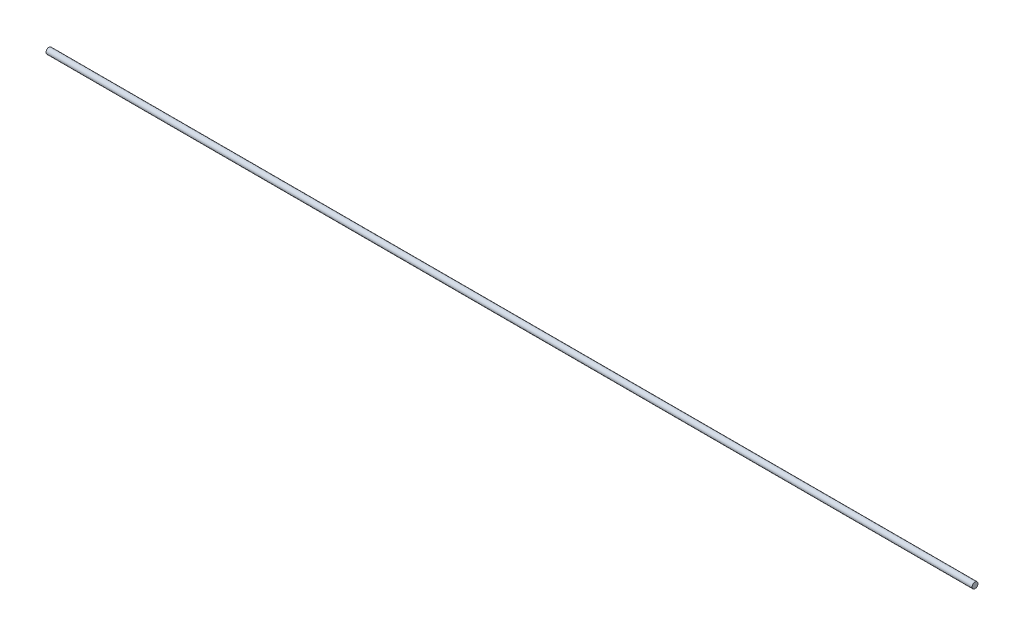
SolidWorks part; units mm, degrees
material "Copper"
ref_plane "Front Plane" through (0, 0, 0) normal (0, 0, 1) x (1, 0, 0)
ref_plane "Top Plane" through (0, 0, 0) normal (0, 1, 0) x (1, 0, 0)
ref_plane "Right Plane" through (0, 0, 0) normal (1, 0, 0) x (0, 0, -1)
sketch "Sketch1" plane through (0, 0, 0) normal (1, 0, 0) x (0, 0, -1)
  circle A0 centre (0, 0) radius 1.5875
  dimension "D1" = 3.175
extrude "Boss-Extrude1" add sketch "Sketch1" along normal blind 499.999
